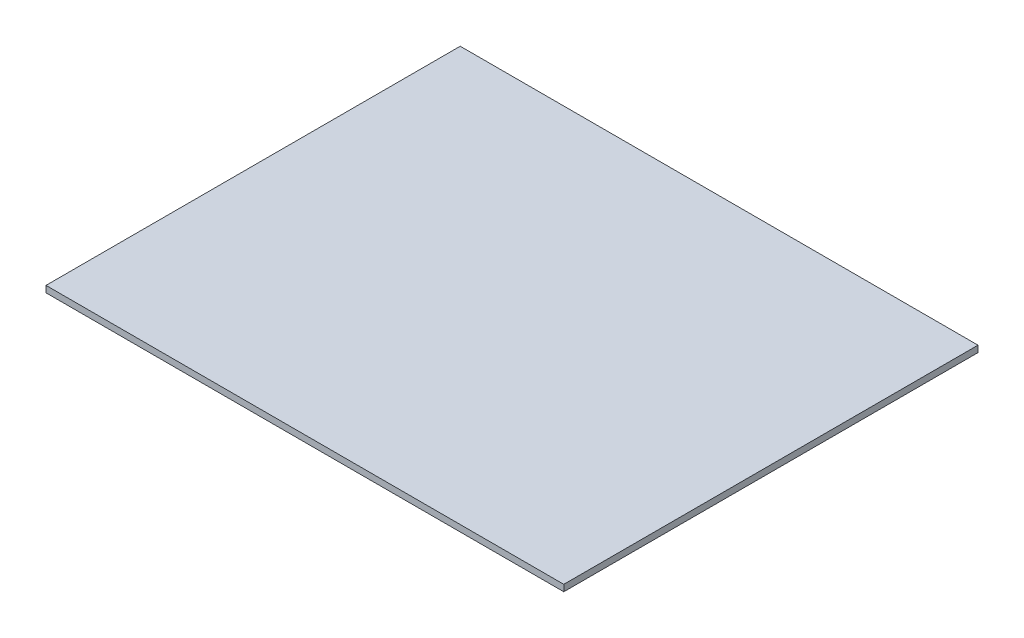
SolidWorks part; units mm, degrees
ref_plane "Front Plane" through (0, 0, 0) normal (0, 0, 1) x (1, 0, 0)
ref_plane "Top Plane" through (0, 0, 0) normal (0, 1, 0) x (1, 0, 0)
ref_plane "Right Plane" through (0, 0, 0) normal (1, 0, 0) x (0, 0, -1)
sketch "Sketch1" plane through (0, 0, 0) normal (0, 1, 0) x (1, 0, 0)
  line L1 (0, 0) -> (254, 0)
  line L2 (0, 0) -> (0, 203.2)
  line L3 (0, 203.2) -> (254, 203.2)
  line L4 (254, 0) -> (254, 203.2)
  dimension "D1" = 254
  dimension "D2" = 203.2
extrude "Boss-Extrude1" add sketch "Sketch1" along normal blind 3.175
